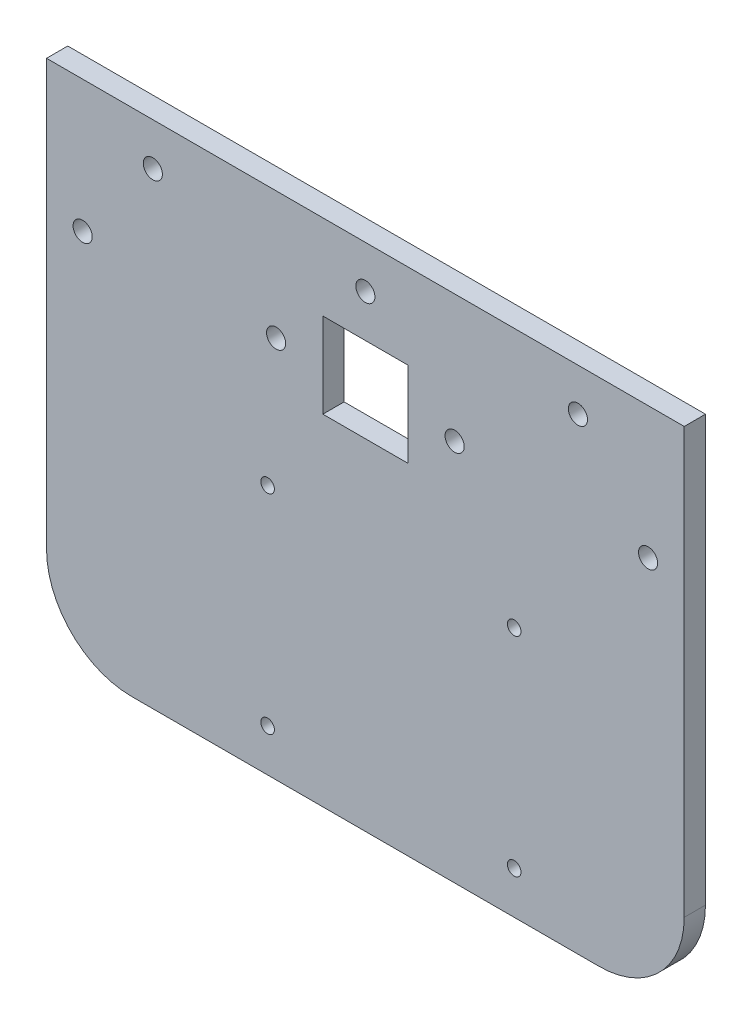
SolidWorks part; units mm, degrees
ref_plane "Plan de face" through (0, 0, 0) normal (0, 0, 1) x (1, 0, 0)
ref_plane "Plan de dessus" through (0, 0, 0) normal (0, 1, 0) x (1, 0, 0)
ref_plane "Plan de droite" through (0, 0, 0) normal (1, 0, 0) x (0, 0, -1)
sketch "Esquisse1" plane through (0, 0, 0) normal (0, 0, 1) x (1, 0, 0)
  line L0 (52, -61) -> (110, -61) construction
  line L1 (0, 0) -> (150, 0)
  line L2 (0, 0) -> (0, -100)
  line L3 (20, -120) -> (130, -120)
  line L4 (150, 0) -> (150, -100)
  line L5 (65, -20) -> (85, -20)
  line L6 (65, -20) -> (65, -40)
  line L7 (65, -40) -> (85, -40)
  line L8 (85, -20) -> (85, -40)
  line L9 (110, -61) -> (110, -110) construction
  line L10 (110, -110) -> (52, -110) construction
  line L11 (52, -110) -> (52, -61) construction
  line L12 (8.5, -31) -> (141.5, -31) construction
  line L13 (25, -10) -> (125, -10) construction
  line L14 (99, -28) -> (93, -32) construction
  line L15 (57, -32) -> (51, -28) construction
  circle A0 centre (52, -61) radius 1.6
  circle A1 centre (110, -61) radius 1.6
  circle A2 centre (110, -110) radius 1.6
  circle A3 centre (52, -110) radius 1.6
  circle A4 centre (8.5, -31) radius 2.25
  circle A5 centre (141.5, -31) radius 2.25
  circle A6 centre (25, -10) radius 2.25
  circle A7 centre (125, -10) radius 2.25
  circle A8 centre (96, -30) radius 2.25
  circle A9 centre (54, -30) radius 2.25
  circle A10 centre (75, -10) radius 2.25
  arc A11 (0, -100) -> (20, -120) centre (20, -100) ccw
  arc A12 (130, -120) -> (150, -100) centre (130, -100) ccw
  point P25 (75, -10)
  point P42 (0, -120)
  dimension "D6" = 3.2
  dimension "D11" = 4.5
  dimension "D19" = 20
  dimension "D1" = 150
  dimension "D2" = 120
  dimension "D3" = 20
  dimension "D4" = 20
  dimension "D5" = 65
  dimension "D7" = 49
  dimension "D8" = 58
  dimension "D9" = 10
  dimension "D10" = 52
  dimension "D12" = 8.5
  dimension "D13" = 8.5
  dimension "D14" = 31
  dimension "D15" = 31
  dimension "D16" = 10
  dimension "D17" = 100
  dimension "D18" = 75
extrude "Boss.-Extru.1" add sketch "Esquisse1" along normal blind 5
